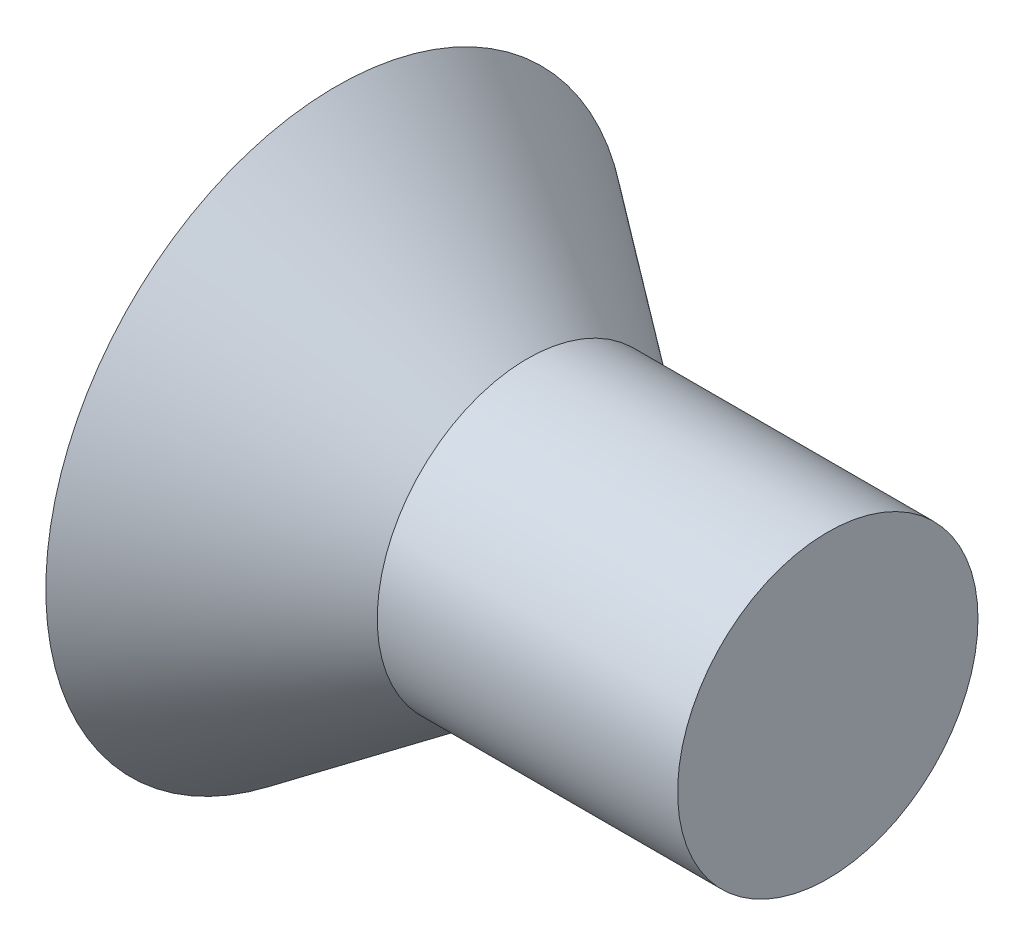
SolidWorks part; units mm, degrees
ref_plane "Front Plane" through (0, 0, 0) normal (0, 0, 1) x (1, 0, 0)
ref_plane "Top Plane" through (0, 0, 0) normal (0, 1, 0) x (1, 0, 0)
ref_plane "Right Plane" through (0, 0, 0) normal (1, 0, 0) x (0, 0, -1)
sketch "Sketch1" plane through (0, 0, 0) normal (0, 0, 1) x (1, 0, 0)
  line L0 (4.91, 0) -> (4.91, 1.5)
  line L1 (4.91, 1.5) -> (1.91, 1.5)
  line L2 (1.91, 1.5) -> (0, 2.9)
  line L3 (0, 2.9) -> (0, 0)
  line L4 (0, -2.9) -> (1.91, -1.5) construction
  line L5 (1.91, -1.5) -> (4.91, -1.5) construction
  line L6 (4.91, -1.5) -> (4.91, 0) construction
  line L7 (4.91, 0) -> (0, 0)
  line L8 (1.91, 1.5) -> (1.91, 0) construction
  line L9 (1.91, 0) -> (1.91, -1.5) construction
  line L10 (0, 0) -> (0, -2.9) construction
  dimension "D1" = 3
  dimension "D2" = 5.8
  dimension "D3" = 3
  dimension "D4" = 4.91
revolve "Revolve2" add sketch "Sketch1" angle 360 about L7
sketch "Sketch2" plane through (0, 0, 0) normal (-1, 0, 0) x (0, 0, 1)
  line L1 (1.1547, 0) -> (0.5774, 1)
  line L2 (0.5774, 1) -> (-0.5774, 1)
  line L3 (-0.5774, 1) -> (-1.1547, 0)
  line L4 (-1.1547, 0) -> (-0.5774, -1)
  line L5 (-0.5774, -1) -> (0.5774, -1)
  line L6 (0.5774, -1) -> (1.1547, 0)
  circle A0 centre (0, 0) radius 1 construction
  point P1 (1.1547, 0)
  dimension "D1" = 2
extrude "Cut-Extrude1" cut sketch "Sketch2" against normal blind 1
